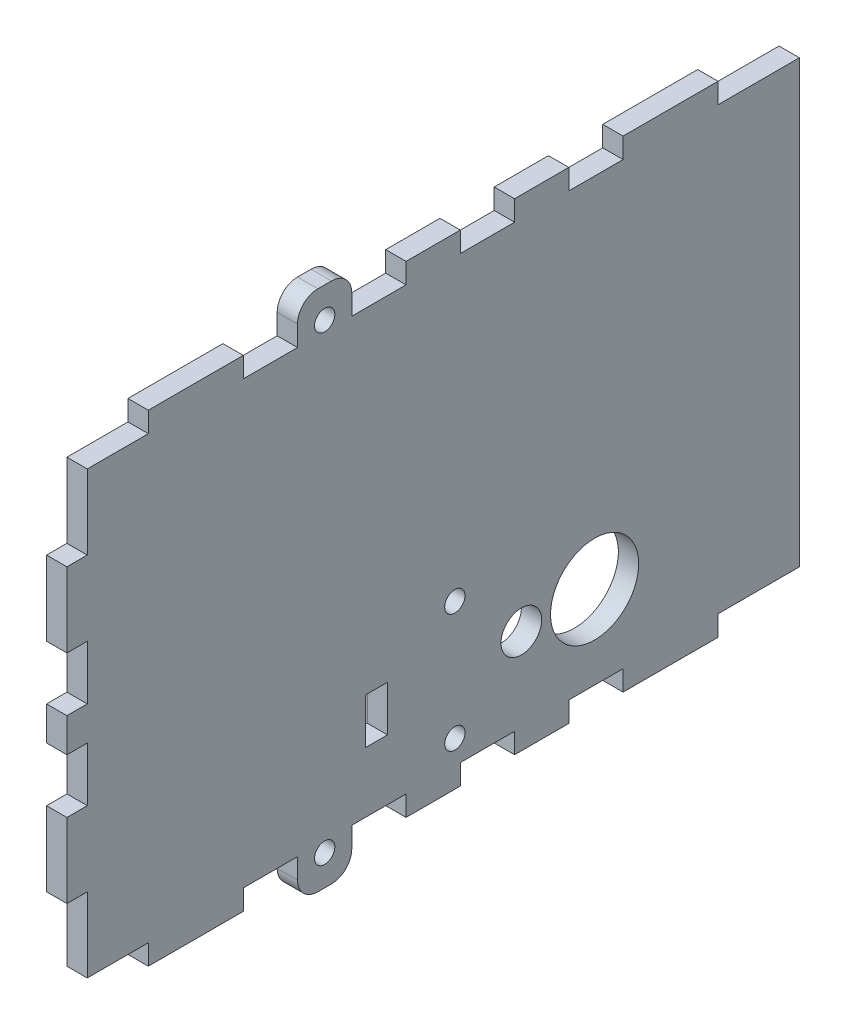
SolidWorks part; units mm, degrees
material "Balsa"
ref_plane "Alzado" through (0, 0, 0) normal (0, 0, 1) x (1, 0, 0)
ref_plane "Planta" through (0, 0, 0) normal (0, 1, 0) x (1, 0, 0)
ref_plane "Vista lateral" through (0, 0, 0) normal (1, 0, 0) x (0, 0, -1)
sketch "Croquis1" plane through (0, 0, 0) normal (1, 0, 0) x (0, 0, -1)
  line L1 (-54, -35.5) -> (54, -35.5)
  line L2 (-54, -35.5) -> (-54, 35.5)
  line L3 (-54, 35.5) -> (54, 35.5)
  line L4 (54, -35.5) -> (54, 35.5)
  line L5 (-54, -35.5) -> (54, 35.5) construction
  line L6 (-54, 35.5) -> (54, -35.5) construction
  point P0 (0, 0)
  dimension "D1" = 108
  dimension "D2" = 71
extrude "Saliente-Extruir1" add sketch "Croquis1" along normal mid plane 3
sketch "Croquis2" plane through (-1.5, 0, 0) normal (-1, 0, 0) x (0, 0, 1)
  line L0 (54, -35.5) -> (-54, -35.5) construction
  line L1 (-42, -32.5) -> (-54, -32.5)
  line L2 (-42, -32.5) -> (-42, -35.5)
  line L3 (-42, -35.5) -> (-54, -35.5)
  line L4 (-54, -32.5) -> (-54, -35.5)
  line L5 (-28, -32.5) -> (-20, -32.5)
  line L6 (-28, -32.5) -> (-28, -35.5)
  line L7 (-28, -35.5) -> (-20, -35.5)
  line L8 (-20, -32.5) -> (-20, -35.5)
  line L9 (-20, -32.5) -> (-20, -35.5) construction
  line L10 (-4, -32.5) -> (-4, -35.5) construction
  line L11 (-12, -32.5) -> (-4, -32.5)
  line L12 (-12, -32.5) -> (-12, -35.5)
  line L13 (-12, -35.5) -> (-4, -35.5)
  line L14 (-4, -32.5) -> (-4, -35.5)
  line L15 (12, -32.5) -> (12, -35.5) construction
  line L16 (4, -32.5) -> (12, -32.5)
  line L17 (4, -32.5) -> (4, -35.5)
  line L18 (4, -35.5) -> (12, -35.5)
  line L19 (12, -32.5) -> (12, -35.5)
  line L20 (28, -32.5) -> (28, -35.5) construction
  line L21 (20, -32.5) -> (28, -32.5)
  line L22 (20, -32.5) -> (20, -35.5)
  line L23 (20, -35.5) -> (28, -35.5)
  line L24 (28, -32.5) -> (28, -35.5)
  line L25 (-54, 0) -> (54, 0) construction
  line L26 (42, -32.5) -> (54, -32.5)
  line L27 (42, -32.5) -> (42, -35.5)
  line L28 (42, -35.5) -> (54, -35.5)
  line L29 (54, -32.5) -> (54, -35.5)
  line L30 (-54, -35.5) -> (-54, 35.5) construction
  line L31 (54, 35.5) -> (54, -35.5) construction
  line L32 (54, 32.5) -> (54, 35.5)
  line L33 (42, 35.5) -> (54, 35.5)
  line L34 (42, 32.5) -> (42, 35.5)
  line L35 (42, 32.5) -> (54, 32.5)
  line L36 (28, 32.5) -> (28, 35.5)
  line L37 (20, 35.5) -> (28, 35.5)
  line L38 (20, 32.5) -> (20, 35.5)
  line L39 (20, 32.5) -> (28, 32.5)
  line L40 (12, 32.5) -> (12, 35.5)
  line L41 (4, 35.5) -> (12, 35.5)
  line L42 (4, 32.5) -> (4, 35.5)
  line L43 (4, 32.5) -> (12, 32.5)
  line L44 (-4, 32.5) -> (-4, 35.5)
  line L45 (-12, 35.5) -> (-4, 35.5)
  line L46 (-12, 32.5) -> (-12, 35.5)
  line L47 (-12, 32.5) -> (-4, 32.5)
  line L48 (-20, 32.5) -> (-20, 35.5)
  line L49 (-28, 35.5) -> (-20, 35.5)
  line L50 (-28, 32.5) -> (-28, 35.5)
  line L51 (-28, 32.5) -> (-20, 32.5)
  line L52 (-54, 32.5) -> (-54, 35.5)
  line L53 (-42, 35.5) -> (-54, 35.5)
  line L54 (-42, 32.5) -> (-42, 35.5)
  line L55 (-42, 32.5) -> (-54, 32.5)
extrude "Cortar-Extruir1" cut sketch "Croquis2" against normal blind 3
sketch "Croquis6" plane through (-1.5, 0, 0) normal (-1, 0, 0) x (0, 0, 1)
  line L0 (54, 32.5) -> (54, -32.5) construction
  line L1 (51, -21.5) -> (54, -21.5)
  line L2 (51, -21.5) -> (51, -35.5)
  line L3 (51, -35.5) -> (54, -35.5)
  line L4 (54, -21.5) -> (54, -35.5)
  line L5 (51, -2.5) -> (54, -2.5)
  line L6 (51, -2.5) -> (51, -10.5)
  line L7 (51, -10.5) -> (54, -10.5)
  line L8 (54, -2.5) -> (54, -10.5)
  line L9 (51, -10.5) -> (54, -10.5) construction
  line L10 (51, 10.5) -> (54, 10.5) construction
  line L11 (51, 2.5) -> (54, 2.5)
  line L12 (51, 2.5) -> (51, 10.5)
  line L13 (51, 10.5) -> (54, 10.5)
  line L14 (54, 2.5) -> (54, 10.5)
  line L16 (51, 21.5) -> (54, 21.5)
  line L17 (51, 21.5) -> (51, 35.5)
  line L18 (51, 35.5) -> (54, 35.5)
  line L19 (54, 21.5) -> (54, 35.5)
extrude "Cortar-Extruir3" cut sketch "Croquis6" against normal blind 3
sketch "Croquis7" plane through (-1.5, 0, 0) normal (-1, 0, 0) x (0, 0, 1)
  line L1 (6.7348, -23.5916) -> (9.9942, -23.5916)
  line L2 (6.7348, -23.5916) -> (6.7348, -16.8678)
  line L3 (6.7348, -16.8678) -> (9.9942, -16.8678)
  line L4 (9.9942, -23.5916) -> (9.9942, -16.8678)
  circle A0 centre (-3.2, -11.5) radius 1.5
  circle A1 centre (-3.2, -29) radius 1.5
  circle A2 centre (-13, -20.25) radius 3
  circle A3 centre (-23.8, -20.25) radius 6.5
  dimension "D1" = 13
  dimension "D2" = 6
extrude "Cortar-Extruir4" cut sketch "Croquis7" against normal blind 23
sketch "Croquis8" plane through (-1.5, 0, 0) normal (-1, 0, 0) x (0, 0, 1)
  line L1 (12, 35.5) -> (20, 35.5)
  line L2 (12, 35.5) -> (12, 38.5)
  line L3 (12, 38.5) -> (20, 38.5)
  line L4 (20, 35.5) -> (20, 38.5)
  dimension "D1" = 3
extrude "Saliente-Extruir2" add sketch "Croquis8" against normal blind 3
fillet "Redondeo2" radius 3 2 edges at (0, 38.5, 20) (0, 38.5, 12)
sketch "Croquis9" plane through (-1.5, 0, 0) normal (-1, 0, 0) x (0, 0, 1)
  line L0 (12, 34) -> (20, 34) construction
  line L1 (12, 32.5) -> (12, 35.5) construction
  line L2 (20, 35.5) -> (20, 32.5) construction
  circle A0 centre (16, 34) radius 1.5
  dimension "D1" = 3
extrude "Cortar-Extruir5" cut sketch "Croquis9" against normal blind 3
mirror "Simetría1" about plane through (0, 0, 0) normal (0, 1, 0) of "Redondeo2", "Cortar-Extruir5", "Saliente-Extruir2"
